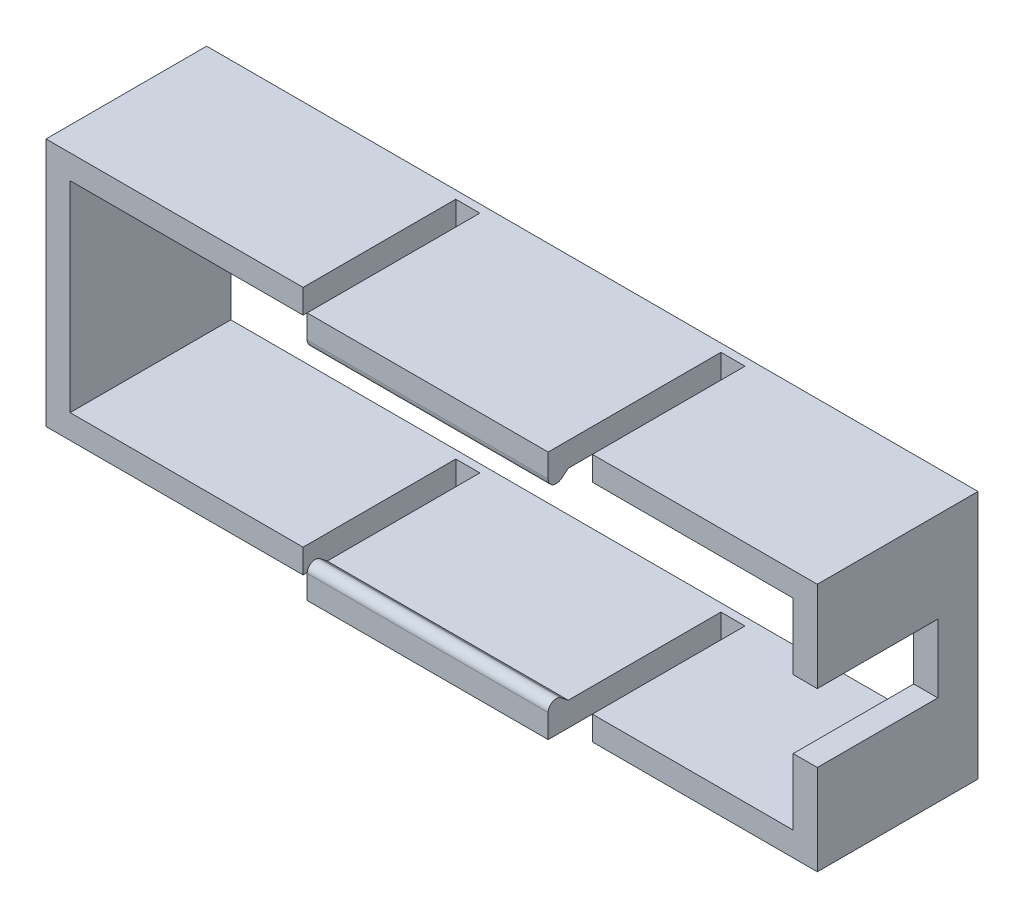
SolidWorks part; units mm, degrees
ref_plane "前视基准面" through (0, 0, 0) normal (0, 0, 1) x (1, 0, 0)
ref_plane "上视基准面" through (0, 0, 0) normal (0, 1, 0) x (1, 0, 0)
ref_plane "右视基准面" through (0, 0, 0) normal (1, 0, 0) x (0, 0, -1)
sketch "草图1" plane through (0, 0, 0) normal (0, 0, 1) x (1, 0, 0)
  line L1 (-45, -12.5) -> (45, -12.5)
  line L2 (-45, -12.5) -> (-45, 12.5)
  line L3 (-45, 12.5) -> (45, 12.5)
  line L4 (45, -12.5) -> (45, 12.5)
  line L5 (-45, -12.5) -> (45, 12.5) construction
  line L6 (-45, 12.5) -> (45, -12.5) construction
  point P0 (0, 0)
  dimension "D1" = 90
  dimension "D2" = 25
extrude "拉伸-薄壁1" add sketch "草图1" along normal blind 20 thin
sketch "草图2" plane through (0, 0, 20) normal (0, 0, 1) x (1, 0, 0)
  line L0 (45, -12.5) -> (45, 12.5) construction
  line L1 (23.513, -4.25) -> (66.487, -4.25)
  line L2 (23.513, -4.25) -> (23.513, 4.25)
  line L3 (23.513, 4.25) -> (66.487, 4.25)
  line L4 (66.487, -4.25) -> (66.487, 4.25)
  line L5 (23.513, -4.25) -> (66.487, 4.25) construction
  line L6 (23.513, 4.25) -> (66.487, -4.25) construction
  point P0 (45, 0)
  dimension "D1" = 8.5
extrude "切除-拉伸1" cut sketch "草图2" against normal blind 15
sketch "草图3" plane through (0, 0, 20) normal (0, 0, 1) x (1, 0, 0)
  line L0 (-13, 36.1235) -> (-13, -29.0869)
  line L1 (-13, -29.0869) -> (17, -29.0869) construction
  line L2 (17, -29.0869) -> (17, 36.1235)
  line L3 (-48, 15.5) -> (-48, -15.5) construction
  dimension "D1" = 30
  dimension "D2" = 35
extrude "切除-拉伸-薄壁1" cut sketch "草图3" against normal blind 19 thin
sketch "草图4" plane through (-13, 0, 0) normal (-1, 0, 0) x (0, 0, 1)
  line L0 (20, 15.5) -> (22.5, 15.5)
  line L1 (22.5, 15.5) -> (22.5, 10.5)
  line L2 (22.5, 10.5) -> (20, 12.5)
  line L3 (20, 15.5) -> (20, 12.5)
  point P8 (22.5, 10.5)
  dimension "D1" = 2.5
  dimension "D2" = 5
extrude "凸台-拉伸1" add sketch "草图4" against normal up to surface (30 mm away) up to face at (17, 14, 10.5)
fillet "圆角1" radius 1 1 edges at (2, 10.5, 22.5)
mirror "镜向2" about plane through (0, 0, 0) normal (0, 1, 0) of "凸台-拉伸1", "圆角1"
